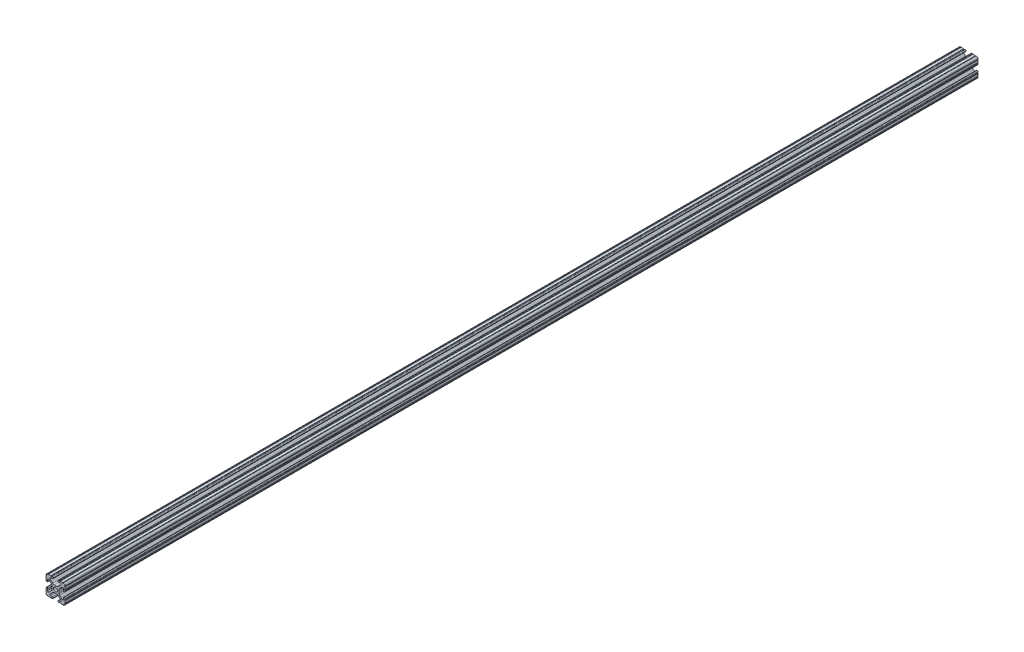
SolidWorks part; units mm, degrees
ref_plane "Front Plane" through (0, 0, 0) normal (0, 0, 1) x (1, 0, 0)
ref_plane "Top Plane" through (0, 0, 0) normal (0, 1, 0) x (1, 0, 0)
ref_plane "Right Plane" through (0, 0, 0) normal (1, 0, 0) x (0, 0, -1)
sketch "Sketch1" plane through (0, 0, 0) normal (0, 0, 1) x (1, 0, 0)
  line L0 (-7.207, 8.7244) -> (-3.8983, 5.4232)
  line L1 (-4.2875, 10.4902) -> (-6.4768, 10.4902)
  line L2 (-3.2385, 11.651) -> (-3.2385, 11.5392)
  line L3 (-5.3171, 12.7) -> (-4.2875, 12.7)
  line L4 (0, 13.4005) -> (0, -14.8534) construction
  line L5 (12.7, 0) -> (-13.9989, 0) construction
  line L6 (-9.5504, 12.7) -> (-6.3331, 12.7)
  line L7 (-12.7, 6.3331) -> (-12.7, 9.5504)
  line L8 (-12.7, 4.2875) -> (-12.7, 5.3171)
  line L9 (-11.5392, 3.2385) -> (-11.651, 3.2385)
  line L10 (-10.4902, 6.4021) -> (-10.4902, 4.2875)
  line L11 (-5.441, 3.8408) -> (-8.7371, 7.1294)
  line L12 (-4.5085, -1.5932) -> (-4.5085, 1.5932)
  line L13 (-1.7093, -4.4958) -> (1.7093, -4.4958)
  line L14 (3.9523, -5.4237) -> (7.1797, -8.6452)
  line L15 (6.4164, -10.4902) -> (4.2875, -10.4902)
  line L16 (3.2385, -11.5392) -> (3.2385, -11.651)
  line L17 (4.2875, -12.7) -> (5.3171, -12.7)
  line L18 (6.3331, -12.7) -> (9.5504, -12.7)
  line L19 (12.7, -9.5504) -> (12.7, -6.3331)
  line L20 (12.7, -5.3171) -> (12.7, -4.2875)
  line L21 (11.651, -3.2385) -> (11.5392, -3.2385)
  line L22 (10.4902, -4.2875) -> (10.4902, -6.4021)
  line L23 (8.7371, -7.1294) -> (5.441, -3.8408)
  line L24 (4.5085, -1.5932) -> (4.5085, 1.5932)
  line L25 (5.441, 3.8408) -> (8.7371, 7.1294)
  line L26 (10.4902, 6.4021) -> (10.4902, 4.2875)
  line L27 (11.5392, 3.2385) -> (11.651, 3.2385)
  line L28 (12.7, 4.2875) -> (12.7, 5.3171)
  line L29 (12.7, 6.3331) -> (12.7, 9.5504)
  line L30 (9.5504, 12.7) -> (6.3331, 12.7)
  line L31 (5.3171, 12.7) -> (4.2875, 12.7)
  line L32 (3.2385, 11.651) -> (3.2385, 11.5392)
  line L33 (4.2875, 10.4902) -> (6.4768, 10.4902)
  line L34 (7.207, 8.7244) -> (3.8983, 5.4232)
  line L35 (1.6558, 4.4958) -> (-1.6558, 4.4958)
  line L36 (-8.7371, -7.1294) -> (-5.441, -3.8408)
  line L37 (-10.4902, -4.2875) -> (-10.4902, -6.4021)
  line L38 (-11.651, -3.2385) -> (-11.5392, -3.2385)
  line L39 (-12.7, -5.3171) -> (-12.7, -4.2875)
  line L40 (-12.7, -9.5504) -> (-12.7, -6.3331)
  line L41 (-6.3331, -12.7) -> (-9.5504, -12.7)
  line L42 (-4.2875, -12.7) -> (-5.3171, -12.7)
  line L43 (-3.2385, -11.5392) -> (-3.2385, -11.651)
  line L44 (-6.4164, -10.4902) -> (-4.2875, -10.4902)
  line L45 (-3.9523, -5.4237) -> (-7.1797, -8.6452)
  arc A0 (-7.207, 8.7244) -> (-6.4768, 10.4902) centre (-6.4768, 9.4563) cw
  arc A1 (-3.2385, 11.5392) -> (-4.2875, 10.4902) centre (-4.2875, 11.5392) cw
  arc A2 (-4.2875, 12.7) -> (-3.2385, 11.651) centre (-4.2875, 11.651) cw
  arc A3 (-5.3171, 12.7) -> (-6.3331, 12.7) centre (-5.8251, 12.7) cw
  arc A4 (-9.5504, 12.7) -> (-10.5664, 12.6998) centre (-10.0584, 12.7) cw
  arc A5 (-12.6998, 10.5664) -> (-10.5664, 12.6998) centre (-10.5918, 10.5918) cw
  arc A6 (-12.6998, 10.5664) -> (-12.7, 9.5504) centre (-12.7, 10.0584) cw
  arc A7 (-12.7, 6.3331) -> (-12.7, 5.3171) centre (-12.7, 5.8251) cw
  arc A8 (-11.651, 3.2385) -> (-12.7, 4.2875) centre (-11.651, 4.2875) cw
  arc A9 (-10.4902, 4.2875) -> (-11.5392, 3.2385) centre (-11.5392, 4.2875) cw
  circle A10 centre (0, 0) radius 2.6035
  arc A11 (-10.4902, 6.4021) -> (-8.7371, 7.1294) centre (-9.4628, 6.4021) cw
  arc A12 (-5.441, 3.8408) -> (-4.5085, 1.5932) centre (-7.6835, 1.5932) cw
  arc A13 (-4.5085, -1.5932) -> (-5.441, -3.8408) centre (-7.6835, -1.5932) cw
  arc A14 (-8.7371, -7.1294) -> (-10.4902, -6.4021) centre (-9.4628, -6.4021) cw
  arc A15 (-1.7093, -4.4958) -> (-3.9523, -5.4237) centre (-1.7093, -7.6708) ccw
  arc A16 (3.9523, -5.4237) -> (1.7093, -4.4958) centre (1.7093, -7.6708) ccw
  arc A17 (6.4164, -10.4902) -> (7.1797, -8.6452) centre (6.4164, -9.4098) ccw
  arc A18 (4.2875, -10.4902) -> (3.2385, -11.5392) centre (4.2875, -11.5392) ccw
  arc A19 (3.2385, -11.651) -> (4.2875, -12.7) centre (4.2875, -11.651) ccw
  arc A20 (6.3331, -12.7) -> (5.3171, -12.7) centre (5.8251, -12.7) ccw
  arc A21 (10.5664, -12.6998) -> (9.5504, -12.7) centre (10.0584, -12.7) ccw
  arc A22 (10.5664, -12.6998) -> (12.6998, -10.5664) centre (10.5918, -10.5918) ccw
  arc A23 (12.7, -9.5504) -> (12.6998, -10.5664) centre (12.7, -10.0584) ccw
  arc A24 (12.7, -5.3171) -> (12.7, -6.3331) centre (12.7, -5.8251) ccw
  arc A25 (12.7, -4.2875) -> (11.651, -3.2385) centre (11.651, -4.2875) ccw
  arc A26 (11.5392, -3.2385) -> (10.4902, -4.2875) centre (11.5392, -4.2875) ccw
  arc A27 (8.7371, -7.1294) -> (10.4902, -6.4021) centre (9.4628, -6.4021) ccw
  arc A28 (4.5085, -1.5932) -> (5.441, -3.8408) centre (7.6835, -1.5932) ccw
  arc A29 (5.441, 3.8408) -> (4.5085, 1.5932) centre (7.6835, 1.5932) ccw
  arc A30 (10.4902, 6.4021) -> (8.7371, 7.1294) centre (9.4628, 6.4021) ccw
  arc A31 (10.4902, 4.2875) -> (11.5392, 3.2385) centre (11.5392, 4.2875) ccw
  arc A32 (11.651, 3.2385) -> (12.7, 4.2875) centre (11.651, 4.2875) ccw
  arc A33 (12.7, 6.3331) -> (12.7, 5.3171) centre (12.7, 5.8251) ccw
  arc A34 (12.6998, 10.5664) -> (12.7, 9.5504) centre (12.7, 10.0584) ccw
  arc A35 (12.6998, 10.5664) -> (10.5664, 12.6998) centre (10.5918, 10.5918) ccw
  arc A36 (9.5504, 12.7) -> (10.5664, 12.6998) centre (10.0584, 12.7) ccw
  arc A37 (5.3171, 12.7) -> (6.3331, 12.7) centre (5.8251, 12.7) ccw
  arc A38 (4.2875, 12.7) -> (3.2385, 11.651) centre (4.2875, 11.651) ccw
  arc A39 (3.2385, 11.5392) -> (4.2875, 10.4902) centre (4.2875, 11.5392) ccw
  arc A40 (7.207, 8.7244) -> (6.4768, 10.4902) centre (6.4768, 9.4563) ccw
  arc A41 (1.6558, 4.4958) -> (3.8983, 5.4232) centre (1.6558, 7.6708) ccw
  arc A42 (-1.6558, 4.4958) -> (-3.8983, 5.4232) centre (-1.6558, 7.6708) cw
  arc A43 (-11.5392, -3.2385) -> (-10.4902, -4.2875) centre (-11.5392, -4.2875) cw
  arc A44 (-12.7, -4.2875) -> (-11.651, -3.2385) centre (-11.651, -4.2875) cw
  arc A45 (-12.7, -5.3171) -> (-12.7, -6.3331) centre (-12.7, -5.8251) cw
  arc A46 (-12.7, -9.5504) -> (-12.6998, -10.5664) centre (-12.7, -10.0584) cw
  arc A47 (-10.5664, -12.6998) -> (-12.6998, -10.5664) centre (-10.5918, -10.5918) cw
  arc A48 (-10.5664, -12.6998) -> (-9.5504, -12.7) centre (-10.0584, -12.7) cw
  arc A49 (-6.3331, -12.7) -> (-5.3171, -12.7) centre (-5.8251, -12.7) cw
  arc A50 (-3.2385, -11.651) -> (-4.2875, -12.7) centre (-4.2875, -11.651) cw
  arc A51 (-4.2875, -10.4902) -> (-3.2385, -11.5392) centre (-4.2875, -11.5392) cw
  arc A52 (-6.4164, -10.4902) -> (-7.1797, -8.6452) centre (-6.4164, -9.4098) cw
  dimension "D1" = 5.207
  dimension "D9" = 14.859
  dimension "D2" = 25.4
  dimension "D3" = 12.7
  dimension "D4" = 6.477
  dimension "D5" = 8.2042
  dimension "D6" = 9.017
  dimension "D8" = 2.2098
  dimension "D10" = 2.2098
extrude "Extrude1" add sketch "Sketch1" against normal blind 1219.2
